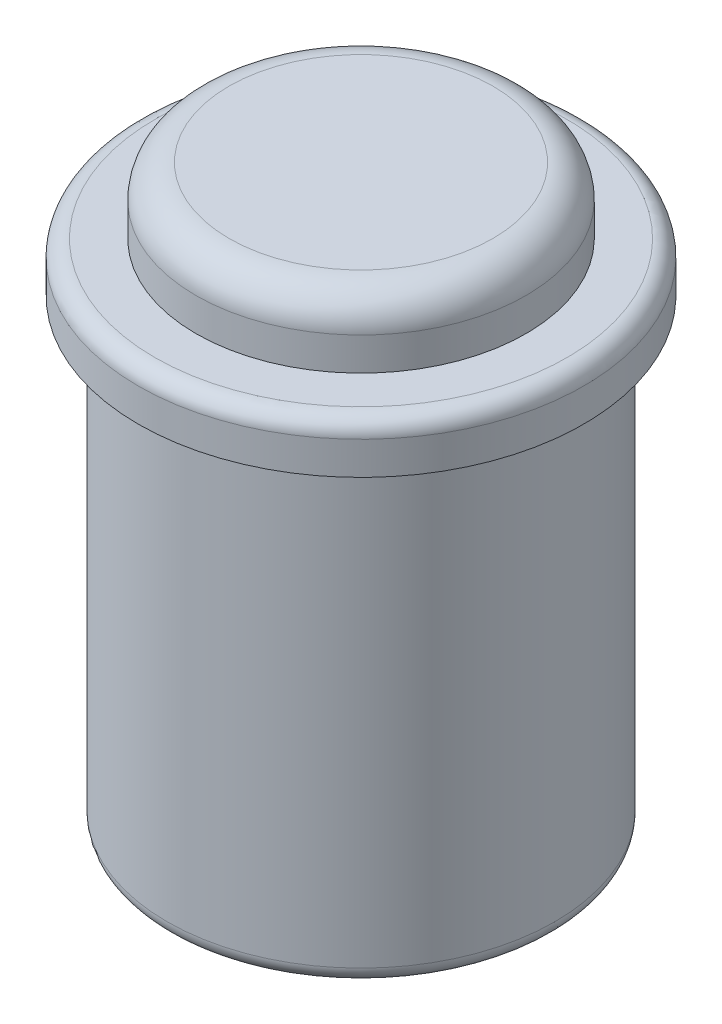
SolidWorks part; units mm, degrees
ref_plane "Plan de face" through (0, 0, 0) normal (0, 0, 1) x (1, 0, 0)
ref_plane "Plan de dessus" through (0, 0, 0) normal (0, 1, 0) x (1, 0, 0)
ref_plane "Plan de droite" through (0, 0, 0) normal (1, 0, 0) x (0, 0, -1)
sketch "Esquisse1" plane through (0, 0, 0) normal (0, 1, 0) x (1, 0, 0)
  circle A0 centre (0, 0) radius 13.5
  dimension "D1" = 27
extrude "Boss.-Extru.1" add sketch "Esquisse1" along normal blind 3
sketch "Esquisse2" plane through (0, 3, 0) normal (0, 1, 0) x (1, 0, 0)
  circle A0 centre (0, 0) radius 10
  dimension "D1" = 20
extrude "Boss.-Extru.2" add sketch "Esquisse2" along normal blind 4
sketch "Esquisse3" plane through (0, 0, 0) normal (0, -1, 0) x (1, 0, 0)
  circle A0 centre (0, 0) radius 11.75
  dimension "D1" = 23.5
extrude "Boss.-Extru.3" add sketch "Esquisse3" along normal blind 28
sketch "Esquisse4" plane through (0, -28, 0) normal (0, -1, 0) x (1, 0, 0)
  line L0 (0, 0) -> (0, -50000) construction
  line L1 (-7.1663, -2.5328) -> (-5.5729, -2.5328)
  line L2 (-7.1663, -2.5328) -> (-7.1663, -2.8813)
  line L3 (-7.1663, -2.8813) -> (-5.5729, -2.8813)
  line L4 (-5.5729, -2.5328) -> (-5.5729, -2.8813)
extrude "Boss.-Extru.4" add sketch "Esquisse4" along normal blind 2.8
mirror "Symétrie1" about plane through (0, 0, 0) normal (1, 0, 0) of "Boss.-Extru.4"
fillet "Congé1" radius 2 1 edges at (0, 7, 10)
fillet "Congé2" radius 1 1 edges at (0, 3, 13.5)
fillet "Congé3" radius 1 1 edges at (0, -28, -11.75)
